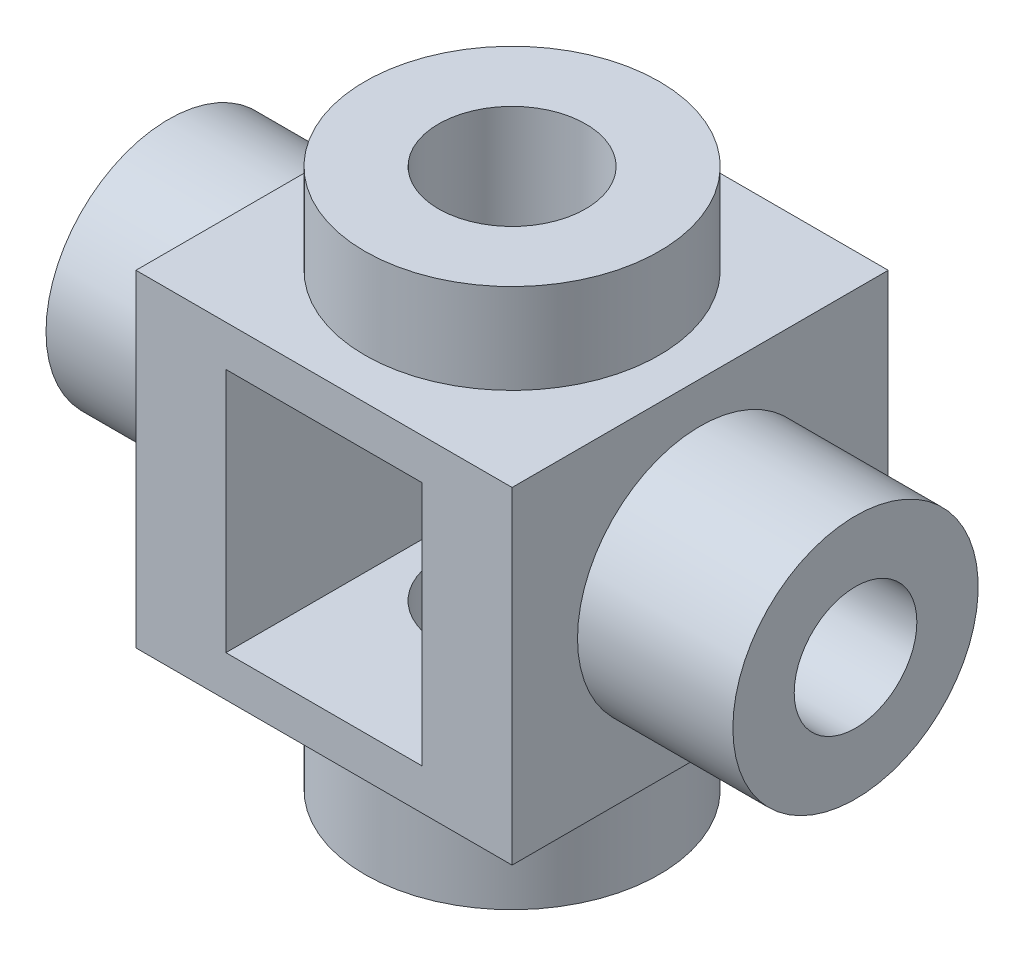
SolidWorks part; units mm, degrees
ref_plane "Front Plane" through (0, 0, 0) normal (0, 0, 1) x (1, 0, 0)
ref_plane "Top Plane" through (0, 0, 0) normal (0, 1, 0) x (1, 0, 0)
ref_plane "Right Plane" through (0, 0, 0) normal (1, 0, 0) x (0, 0, -1)
sketch "Sketch1" plane through (0, 0, 0) normal (1, 0, 0) x (0, 0, -1)
  circle A0 centre (0, 0) radius 15
  circle A1 centre (0, 0) radius 7.5
  dimension "D1" = 30
  dimension "D2" = 15
extrude "Boss-Extrude1" add sketch "Sketch1" along normal mid plane 84
sketch "Sketch2" plane through (0, 0, 0) normal (0, 0, 1) x (1, 0, 0)
  line L1 (-23, 20) -> (23, 20)
  line L2 (-23, 20) -> (-23, -20)
  line L3 (-23, -20) -> (23, -20)
  line L4 (23, 20) -> (23, -20)
  line L5 (-23, 20) -> (23, -20) construction
  line L6 (-23, -20) -> (23, 20) construction
  point P0 (0, 0)
  dimension "D1" = 46
  dimension "D2" = 40
extrude "Boss-Extrude2" add sketch "Sketch2" along normal mid plane 46
sketch "Sketch3" plane through (0, 0, 23) normal (0, 0, 1) x (1, 0, 0)
  line L1 (-12, 15) -> (12, 15)
  line L2 (-12, 15) -> (-12, -15)
  line L3 (-12, -15) -> (12, -15)
  line L4 (12, 15) -> (12, -15)
  line L5 (-12, 15) -> (12, -15) construction
  line L6 (-12, -15) -> (12, 15) construction
  point P0 (0, 0)
  dimension "D1" = 24
  dimension "D2" = 30
extrude "Cut-Extrude1" cut sketch "Sketch3" against normal through all
hole_wizard "Hole1" positions "Sketch4" profile "Sketch5" legacy end condition through all
sketch "Sketch4" plane through (42, 0, 0) normal (1, 0, 0) x (0, 0, -1)
  point P0 (0, 0)
sketch "Sketch5" plane through (42, 0, 0) normal (0, 1, 0) x (0, 0, -1)
  line L0 (0, 0) -> (0, 84)
  line L1 (0, 84) -> (7.5, 84)
  line L2 (7.5, 84) -> (7.5, 0)
  line L3 (7.5, 0) -> (0, 0)
  line L4 (0, 110) -> (0, -10) construction
  dimension "Diameter" = 15
  dimension "Depth" = 84
sketch "Sketch6" plane through (0, 20, 0) normal (0, 1, 0) x (1, 0, 0)
  circle A0 centre (0, 0) radius 18
  dimension "D1" = 36
extrude "Boss-Extrude3" add sketch "Sketch6" along normal blind 11 and the other way blind 55
sketch "Sketch7" plane through (0, 0, 23) normal (0, 0, 1) x (1, 0, 0)
  line L1 (-12, 15) -> (12, 15)
  line L2 (-12, 15) -> (-12, -15)
  line L3 (-12, -15) -> (12, -15)
  line L4 (12, 15) -> (12, -15)
  line L5 (-12, 15) -> (12, -15) construction
  line L6 (-12, -15) -> (12, 15) construction
  point P0 (0, 0)
extrude "Cut-Extrude2" cut sketch "Sketch7" against normal through all
hole_wizard "Hole2" positions "Sketch8" profile "Sketch9" legacy end condition through all
sketch "Sketch8" plane through (0, 31, 0) normal (0, 1, 0) x (1, 0, 0)
  point P0 (0, 0)
sketch "Sketch9" plane through (0, 31, 0) normal (1, 0, 0) x (0, 0, 1)
  line L0 (0, 0) -> (0, 66)
  line L1 (0, 66) -> (9, 66)
  line L2 (9, 66) -> (9, 0)
  line L3 (9, 0) -> (0, 0)
  line L4 (0, 110) -> (0, -10) construction
  dimension "Diameter" = 18
  dimension "Depth" = 66
